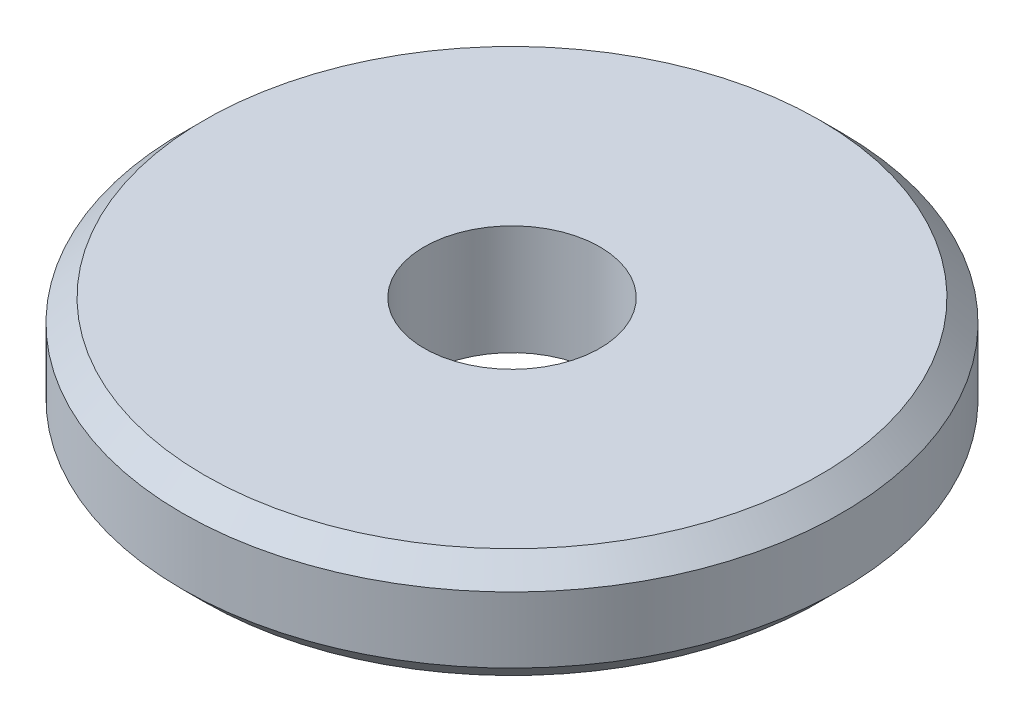
SolidWorks part; units mm, degrees
ref_plane "前视基准面" through (0, 0, 0) normal (0, 0, 1) x (1, 0, 0)
ref_plane "上视基准面" through (0, 0, 0) normal (0, 1, 0) x (1, 0, 0)
ref_plane "右视基准面" through (0, 0, 0) normal (1, 0, 0) x (0, 0, -1)
sketch "草图1" plane through (0, 0, 0) normal (0, 1, 0) x (1, 0, 0)
  circle A0 centre (0, 0) radius 15
extrude "凸台-拉伸1" add sketch "草图1" along normal blind 5
chamfer "倒角1" distance 1 angle 45 2 edges at (0, 0, 15) (0, 5, 15)
sketch "草图2" plane through (0, 0, 0) normal (0, -1, 0) x (1, 0, 0)
  circle A0 centre (0, 0) radius 4
extrude "切除-拉伸1" cut sketch "草图2" against normal through all
